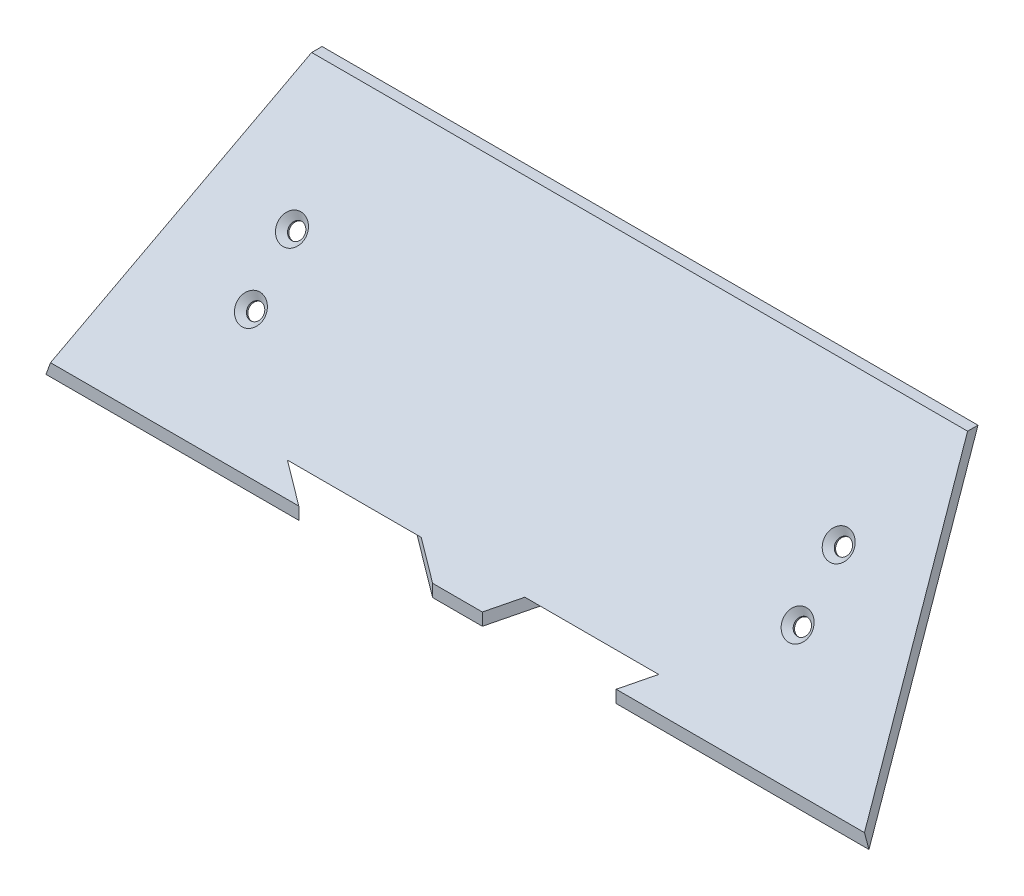
SolidWorks part; units mm, degrees
material "Delrin 2700 NC010, Low Viscosity Acetal Copolymer (SS)"
ref_plane "Front Plane" through (0, 0, 0) normal (0, 0, 1) x (1, 0, 0)
ref_plane "Top Plane" through (0, 0, 0) normal (0, 1, 0) x (1, 0, 0)
ref_plane "Right Plane" through (0, 0, 0) normal (1, 0, 0) x (0, 0, -1)
sketch "Sketch2" plane through (0, 0, 0) normal (1, 0, 0) x (0, 0, -1)
  line L0 (0, 0) -> (-2.3622, 0)
  line L1 (-2.3622, 0) -> (45.4805, 57.0167)
  line L2 (45.4805, 57.0167) -> (47.8427, 57.0167)
  line L3 (47.8427, 57.0167) -> (0, 0)
  dimension "D1" = 50
  dimension "D2" = 74.43
  dimension "D3" = 2.3622
extrude "Boss-Extrude1" add sketch "Sketch2" along normal blind 186.9479
sketch "Sketch3" plane through (0, 0, 0) normal (-1, 0, 0) x (0, 0, 1)
  line L0 (-4.1057, 4.893) -> (-4.1057, 7.7082)
  line L1 (-45.4805, 57.0167) -> (2.3622, 0) construction
  line L2 (-4.1057, 7.7082) -> (2.3622, 0)
  line L3 (2.3622, 0) -> (0, 0)
  line L4 (0, 0) -> (-4.1057, 4.893)
  line L5 (0, 0) -> (-47.8427, 57.0167) construction
  line L6 (-4.1057, 2.5396) -> (-4.1057, -12.9833) construction
extrude "Cut-Extrude1" cut sketch "Sketch3" against normal through all
sketch "Sketch4" plane through (93.4965, -1.9814, -4.1057) normal (0, 0, -1) x (-1, 0, 0)
  line L0 (93.4965, 58.998) -> (74.525, 58.998)
  line L1 (-93.4515, 58.998) -> (93.4965, 58.998) construction
  line L3 (74.525, 58.998) -> (93.4965, 6.8743)
  line L4 (93.4965, 6.8743) -> (93.4965, 58.998)
  line L5 (-93.4515, 6.8743) -> (-93.4515, 58.998)
  line L6 (-93.4515, 58.998) -> (-74.48, 58.998)
  line L7 (-74.48, 58.998) -> (-93.4515, 6.8743)
  dimension "D1" = 20
  dimension "D2" = 20
extrude "Cut-Extrude2" cut sketch "Sketch4" along normal through all
hole_wizard "CSK for M3 Flat Head Machine Screw1" positions "Sketch5" profile "Sketch6" countersink size "M3" standard "ANSI Metric"
sketch "Sketch5" plane through (0, 1.1632, 1.3862) normal (0, 0.6428, 0.766) x (1, 0, 0)
  point P0 (31.3777, 46.6549)
  point P2 (31.3777, 32.1455)
sketch "Sketch6" plane through (31.3777, 36.9029, -28.603) normal (1, 0, 0) x (0, -0.766, 0.6428)
  line L0 (0, 0) -> (0, 5)
  line L1 (0, 5) -> (1.75, 5)
  line L2 (1.75, 5) -> (1.75, 1.4)
  line L3 (1.75, 1.4) -> (3.15, 0)
  line L5 (3.15, 0) -> (0, 0)
  line L6 (-1.75, 1.4) -> (-3.15, 0) construction
  line L10 (0, 5) -> (-1.75, 5) construction
  line L11 (0, -6.35) -> (0, 107.95) construction
  dimension "Hole Dia." = 3.5
  dimension "Hole Depth" = 5
  dimension "Near C'Sink Dia." = 6.3
  dimension "Near C'Sink Angle" = 90
  dimension "Drill Angle" = 180
ref_plane "Plane1" through (93.474, 0, 0) normal (1, 0, 0) x (0, 0, -1)
mirror "Mirror1" about plane through (93.474, 0, 0) normal (1, 0, 0) of "CSK for M3 Flat Head Machine Screw1"
ref_plane "Plane2" through (112.633, 0, -65.0287) normal (-0.866, 0, 0.5) x (0.5, 0, 0.866)
sketch "Sketch7" plane through (112.633, 0, -65.0287) normal (-0.866, 0, 0.5) x (0.5, 0, 0.866)
  line L0 (46.0064, 4.9186) -> (46.0064, 3.9186)
  line L1 (61.2064, 11.9186) -> (46.0064, 11.9186)
  line L2 (61.2064, 11.9186) -> (61.2064, 4.9186)
  line L3 (61.2064, 4.9186) -> (46.0064, 4.9186)
  line L4 (46.0064, 11.9186) -> (46.0064, 4.9186)
  line L5 (46.0064, 3.9186) -> (61.2064, 3.9186)
  line L6 (61.2064, 3.9186) -> (61.2064, 4.9186)
  dimension "D1" = 1
extrude "Cut-Extrude3" cut sketch "Sketch7" along normal up to surface (8.7674 mm away) contours L1 L4 L3 L2 | L5 L6 L3 L0
mirror "Mirror2" about plane through (93.474, 0, 0) normal (1, 0, 0) of "Cut-Extrude3"
